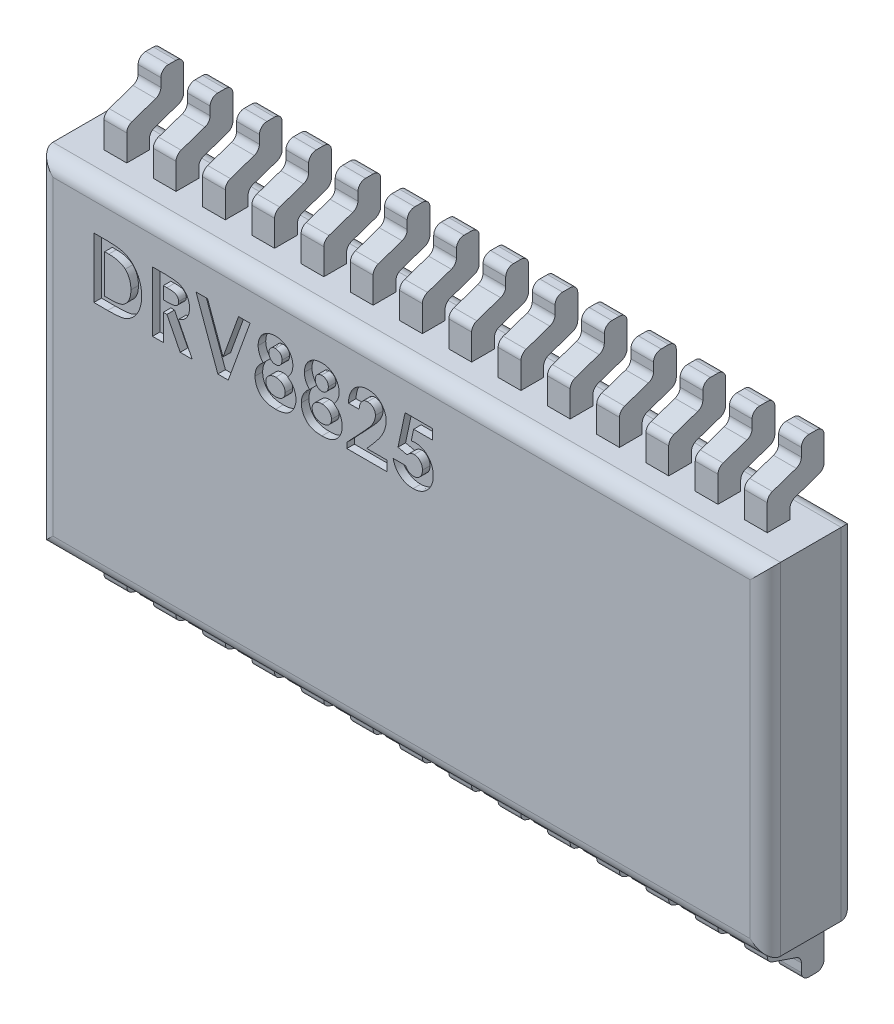
SolidWorks part; units mm, degrees
ref_plane "Front Plane" through (0, 0, 0) normal (0, 0, 1) x (1, 0, 0)
ref_plane "Top Plane" through (0, 0, 0) normal (0, 1, 0) x (1, 0, 0)
ref_plane "Right Plane" through (0, 0, 0) normal (1, 0, 0) x (0, 0, -1)
sketch "Sketch1" plane through (0, 0, 0) normal (0, 0, 1) x (1, 0, 0)
  line L1 (-4.8, 2.25) -> (4.8, 2.25)
  line L2 (-4.8, 2.25) -> (-4.8, -2.25)
  line L3 (-4.8, -2.25) -> (4.8, -2.25)
  line L4 (4.8, 2.25) -> (4.8, -2.25)
  line L5 (-4.8, 2.25) -> (4.8, -2.25) construction
  line L6 (-4.8, -2.25) -> (4.8, 2.25) construction
  point P0 (0, 0)
  dimension "D1" = 9.6
  dimension "D2" = 4.5
extrude "Boss-Extrude1" add sketch "Sketch1" along normal blind 1.2
ref_plane "Plane1" through (0.175, 0, 0) normal (1, 0, 0) x (0, 0, -1)
sketch "Sketch2" plane through (0.175, 0, 0) normal (1, 0, 0) x (0, 0, -1)
  line L0 (-0.75, 2.25) -> (-0.75, 2.5931)
  line L1 (-1.2, 2.25) -> (0, 2.25) construction
  line L2 (-0.6823, 2.6878) -> (-0.3677, 2.795)
  line L3 (-0.3, 2.8896) -> (-0.3, 3)
  line L4 (-0.2, 3.1) -> (-0.1, 3.1)
  line L5 (0, 3) -> (0, 2.6749)
  line L6 (-0.0677, 2.5803) -> (-0.3823, 2.4731)
  line L7 (-0.45, 2.3784) -> (-0.45, 2.25)
  line L8 (-0.45, 2.25) -> (-0.75, 2.25)
  line L9 (0, 0) -> (-1.954, 0) construction
  line L10 (0, -2.25) -> (0, 2.25) construction
  line L11 (-0.45, -2.25) -> (-0.75, -2.25)
  line L12 (-0.45, -2.3784) -> (-0.45, -2.25)
  line L13 (-0.0677, -2.5803) -> (-0.3823, -2.4731)
  line L14 (0, -3) -> (0, -2.6749)
  line L15 (-0.2, -3.1) -> (-0.1, -3.1)
  line L16 (-0.3, -2.8896) -> (-0.3, -3)
  line L17 (-0.6823, -2.6878) -> (-0.3677, -2.795)
  line L18 (-0.75, -2.25) -> (-0.75, -2.5931)
  arc A0 (-0.1, 3.1) -> (0, 3) centre (-0.1, 3) cw
  arc A1 (-0.2, 3.1) -> (-0.3, 3) centre (-0.2, 3) ccw
  arc A2 (-0.3677, 2.795) -> (-0.3, 2.8896) centre (-0.4, 2.8896) ccw
  arc A3 (0, 2.6749) -> (-0.0677, 2.5803) centre (-0.1, 2.6749) cw
  arc A4 (-0.3823, 2.4731) -> (-0.45, 2.3784) centre (-0.35, 2.3784) ccw
  arc A5 (-0.6823, 2.6878) -> (-0.75, 2.5931) centre (-0.65, 2.5931) ccw
  arc A6 (-0.6823, -2.6878) -> (-0.75, -2.5931) centre (-0.65, -2.5931) cw
  arc A7 (-0.3823, -2.4731) -> (-0.45, -2.3784) centre (-0.35, -2.3784) cw
  arc A8 (0, -2.6749) -> (-0.0677, -2.5803) centre (-0.1, -2.6749) ccw
  arc A9 (-0.3677, -2.795) -> (-0.3, -2.8896) centre (-0.4, -2.8896) cw
  arc A10 (-0.2, -3.1) -> (-0.3, -3) centre (-0.2, -3) cw
  arc A11 (-0.1, -3.1) -> (0, -3) centre (-0.1, -3) ccw
  point P25 (-0.45, 2.45)
  point P48 (-0.45, -2.45)
  dimension "D7" = 0.1
  dimension "D1" = 3.1
  dimension "D2" = 0.3
  dimension "D3" = 0.3
  dimension "D4" = 0.45
  dimension "D5" = 0.3
  dimension "D6" = 0.2
extrude "Boss-Extrude2" add sketch "Sketch2" along normal blind 0.3
pattern_linear "LPattern1" count 8 spacing 0.65 along (-1, 0, 0) count 7 spacing 0.65 along (1, 0, 0) of "Boss-Extrude2"
fillet "Fillet1" radius 0.2 8 edges at (4.8, 0, 0) (4.8, 0, 1.2) (-4.8, 0, 1.2) (-4.8, 0, 0) (0, 2.25, 0) (0, 2.25, 1.2) (0, -2.25, 0) (0, -2.25, 1.2)
sketch "Sketch3" plane through (0, 0, 1.2) normal (0, 0, 1) x (1, 0, 0)
  text T0 "DRV8825" font "Century Gothic" height in points 3
extrude "Cut-Extrude1" cut sketch "Sketch3" against normal blind 0.1
